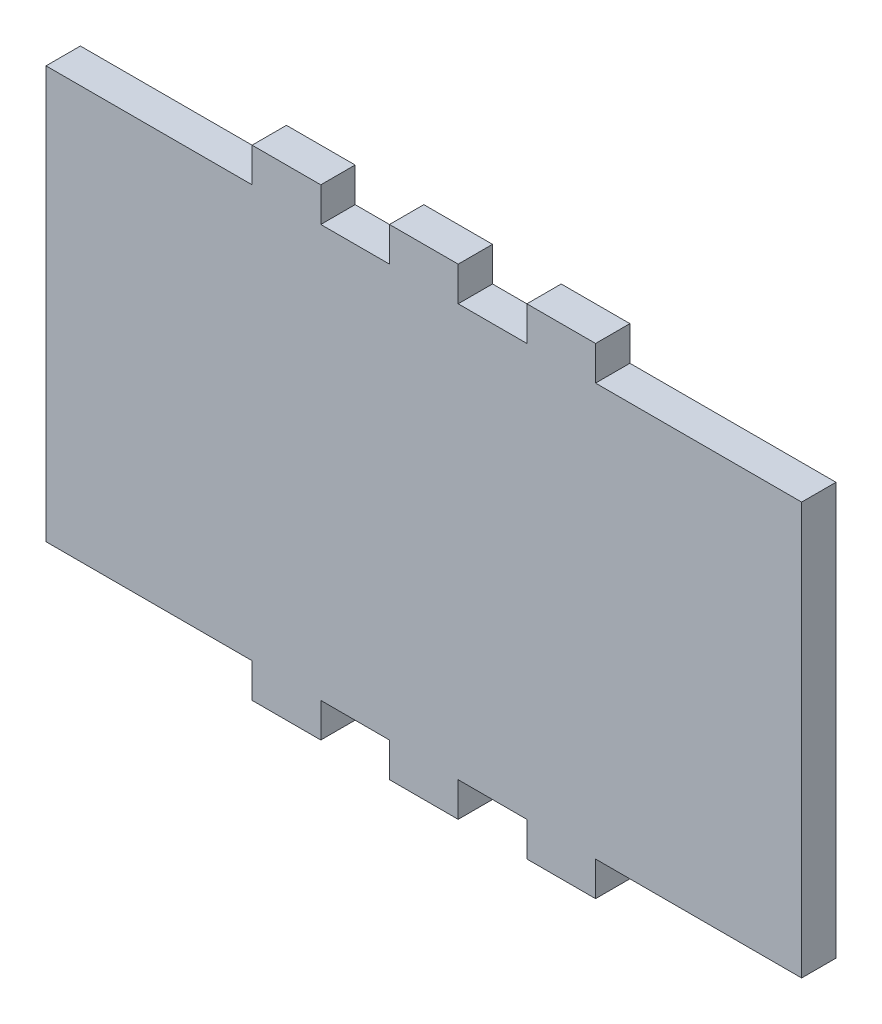
SolidWorks part; units mm, degrees
ref_plane "Front Plane" through (0, 0, 0) normal (0, 0, 1) x (1, 0, 0)
ref_plane "Top Plane" through (0, 0, 0) normal (0, 1, 0) x (1, 0, 0)
ref_plane "Right Plane" through (0, 0, 0) normal (1, 0, 0) x (0, 0, -1)
sketch "Sketch1" plane through (0, 0, 0) normal (0, 0, 1) x (1, 0, 0)
  line L13 (-34.925, -19.05) -> (34.925, -19.05) construction
  line L14 (-34.925, -19.05) -> (-34.925, 19.05)
  line L15 (-34.925, 19.05) -> (34.925, 19.05) construction
  line L16 (34.925, -19.05) -> (34.925, 19.05)
  line L17 (-34.925, -19.05) -> (34.925, 19.05) construction
  line L18 (-34.925, 19.05) -> (34.925, -19.05) construction
  line L19 (-15.875, 19.05) -> (-15.875, 22.225)
  line L20 (-15.875, 22.225) -> (-9.525, 22.225)
  line L21 (-9.525, 22.225) -> (-9.525, 19.05)
  line L22 (-9.525, 19.05) -> (-3.175, 19.05)
  line L23 (-3.175, 19.05) -> (-3.175, 22.225)
  line L24 (-3.175, 22.225) -> (3.175, 22.225)
  line L25 (3.175, 22.225) -> (3.175, 19.05)
  line L26 (3.175, 19.05) -> (9.525, 19.05)
  line L27 (9.525, 19.05) -> (9.525, 22.225)
  line L28 (9.525, 22.225) -> (15.875, 22.225)
  line L29 (15.875, 22.225) -> (15.875, 19.05)
  line L31 (-34.925, 0) -> (34.925, 0) construction
  line L32 (15.875, -22.225) -> (15.875, -19.05)
  line L33 (9.525, -19.05) -> (9.525, -22.225)
  line L34 (9.525, -22.225) -> (15.875, -22.225)
  line L35 (-3.175, -22.225) -> (3.175, -22.225)
  line L36 (3.175, -22.225) -> (3.175, -19.05)
  line L37 (-3.175, -19.05) -> (-3.175, -22.225)
  line L38 (-9.525, -22.225) -> (-9.525, -19.05)
  line L39 (-15.875, -19.05) -> (-15.875, -22.225)
  line L40 (-15.875, -22.225) -> (-9.525, -22.225)
  line L42 (-9.525, -19.05) -> (-3.175, -19.05)
  line L43 (9.525, -19.05) -> (3.175, -19.05)
  line L45 (-15.875, 19.05) -> (-34.925, 19.05)
  line L46 (15.875, 19.05) -> (34.925, 19.05)
  line L47 (34.925, -19.05) -> (15.875, -19.05)
  line L48 (-15.875, -19.05) -> (-34.925, -19.05)
  point P0 (0, 0)
  dimension "D1" = 69.85
  dimension "D2" = 38.1
  dimension "D3" = 6.35
  dimension "D4" = 3.175
  dimension "D5" = 6.35
extrude "Boss-Extrude1" add sketch "Sketch1" along normal blind 3.175
